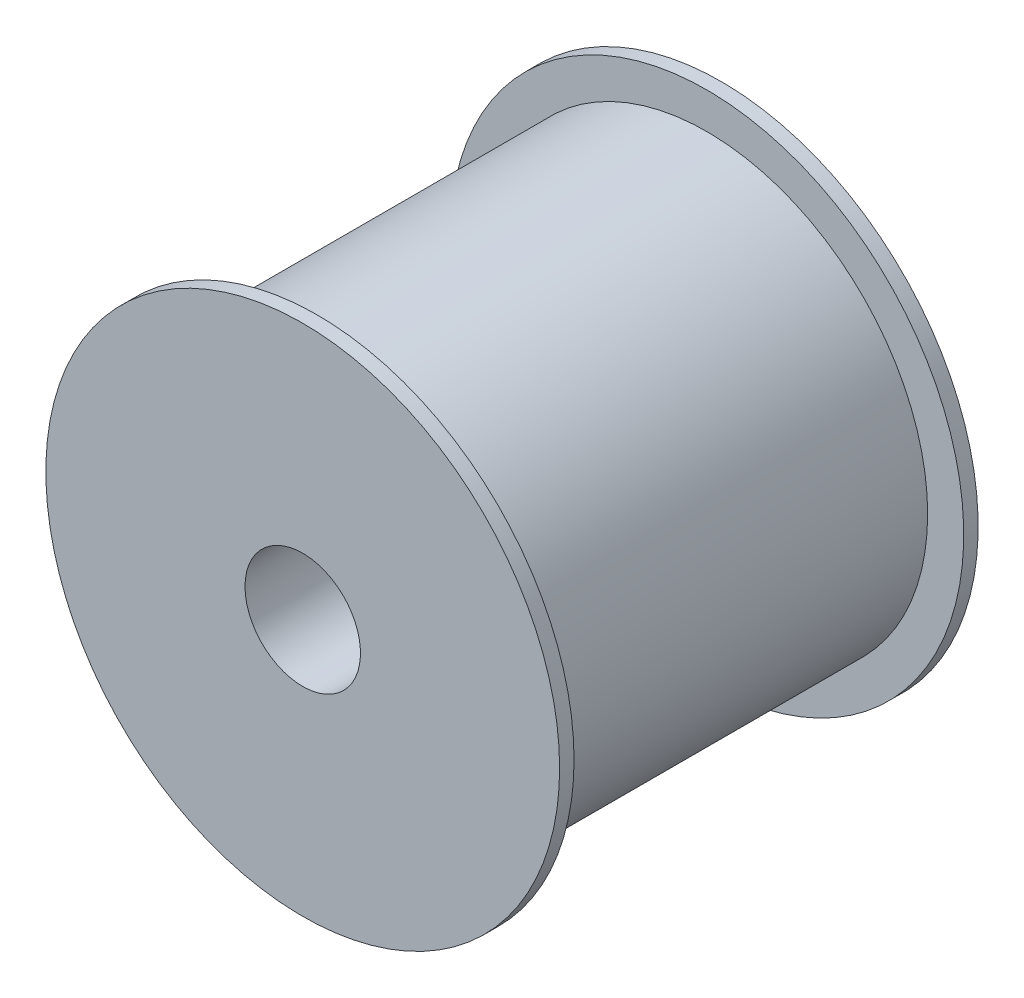
SolidWorks part; units mm, degrees
ref_plane "Front Plane" through (0, 0, 0) normal (0, 0, 1) x (1, 0, 0)
ref_plane "Top Plane" through (0, 0, 0) normal (0, 1, 0) x (1, 0, 0)
ref_plane "Right Plane" through (0, 0, 0) normal (1, 0, 0) x (0, 0, -1)
sketch "Sketch1" plane through (0, 0, 0) normal (0, 0, 1) x (1, 0, 0)
  circle A0 centre (0, 0) radius 15.3
  dimension "D1" = 30.6
extrude "Boss-Extrude1" add sketch "Sketch1" along normal blind 27
sketch "Sketch2" plane through (0, 0, 27) normal (0, 0, 1) x (1, 0, 0)
  circle A0 centre (0, 0) radius 17.8
  circle A1 centre (0, 0) radius 15.3 construction
  dimension "D1" = 2.5
extrude "Boss-Extrude2" add sketch "Sketch2" along normal blind 1
sketch "Sketch6" plane through (0, 0, 0) normal (0, 0, -1) x (-1, 0, 0)
  circle A2 centre (0, 0) radius 17.8
  circle A3 centre (0, 0) radius 15.3 construction
  dimension "D1" = 2.5
extrude "Boss-Extrude4" add sketch "Sketch6" along normal blind 1
sketch "Sketch7" plane through (0, 0, -1) normal (0, 0, -1) x (-1, 0, 0)
  circle A0 centre (0, 0) radius 4
  dimension "D1" = 8
extrude "Cut-Extrude1" cut sketch "Sketch7" against normal through all
sketch "Sketch8" plane through (0, 0, -1) normal (0, 0, -1) x (-1, 0, 0)
  line L0 (0, 0) -> (32.8677, 0)
